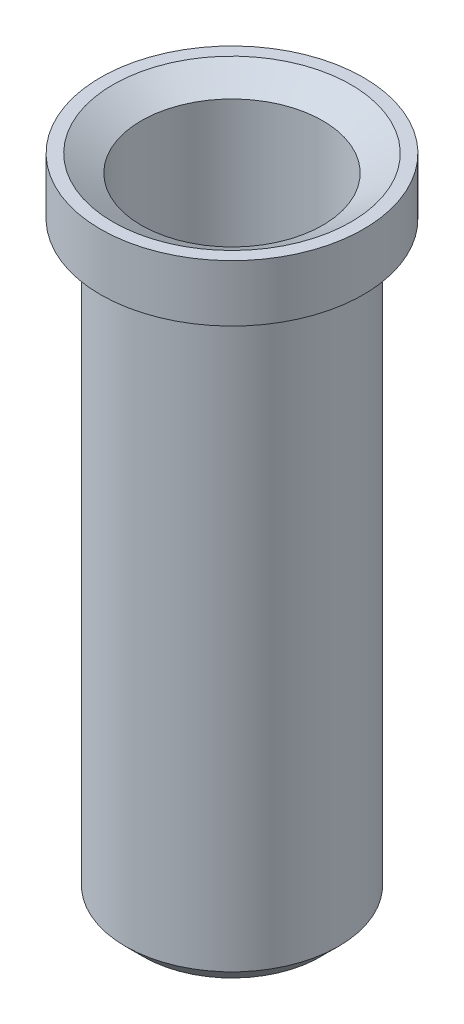
SolidWorks part; units mm, degrees
ref_plane "前视基准面" through (0, 0, 0) normal (0, 0, 1) x (1, 0, 0)
ref_plane "上视基准面" through (0, 0, 0) normal (0, 1, 0) x (1, 0, 0)
ref_plane "右视基准面" through (0, 0, 0) normal (1, 0, 0) x (0, 0, -1)
sketch "草图1" plane through (0, 0, 0) normal (0, 0, 1) x (1, 0, 0)
  line L0 (0, 8.2388) -> (0, -6.3059) construction
  line L1 (0, -5.25) -> (-0.94, -5.25)
  line L2 (-0.94, -5.25) -> (-0.94, 0)
  line L3 (-0.94, 0) -> (-1.16, 0)
  line L4 (-1.16, 0) -> (-1.16, 0.5)
  line L5 (-1.16, 0.5) -> (-1.05, 0.5)
  line L6 (-1.05, 0.5) -> (-0.8, 0.3497)
  line L10 (-0.8, 0.3497) -> (-0.8, -4)
  line L11 (-0.8, -4) -> (0, -4.5456)
  line L12 (5.0295, 0) -> (-9.301, 0) construction
  line L13 (0, -5.25) -> (0, -4.5456)
  point P5 (-0.8736, 0.5)
  point P10 (-0.775, 0.3497)
  point P11 (0, -4.5456)
  point P15 (-0.47, -5.25)
  point P18 (0, 0)
  point P23 (-1.16, 0.25)
  dimension "D1" = 5.25
  dimension "D2" = 0.5
  dimension "D3" = 0.8
  dimension "D4" = 1.05
  dimension "D5" = 0.94
  dimension "D6" = 1.16
  dimension "D7" = 4.5
revolve "旋转1" add sketch "草图1" angle 360 about L0
chamfer "倒角1" distance 0.16 angle 45 1 edges at (0, -5.25, 0.94)
